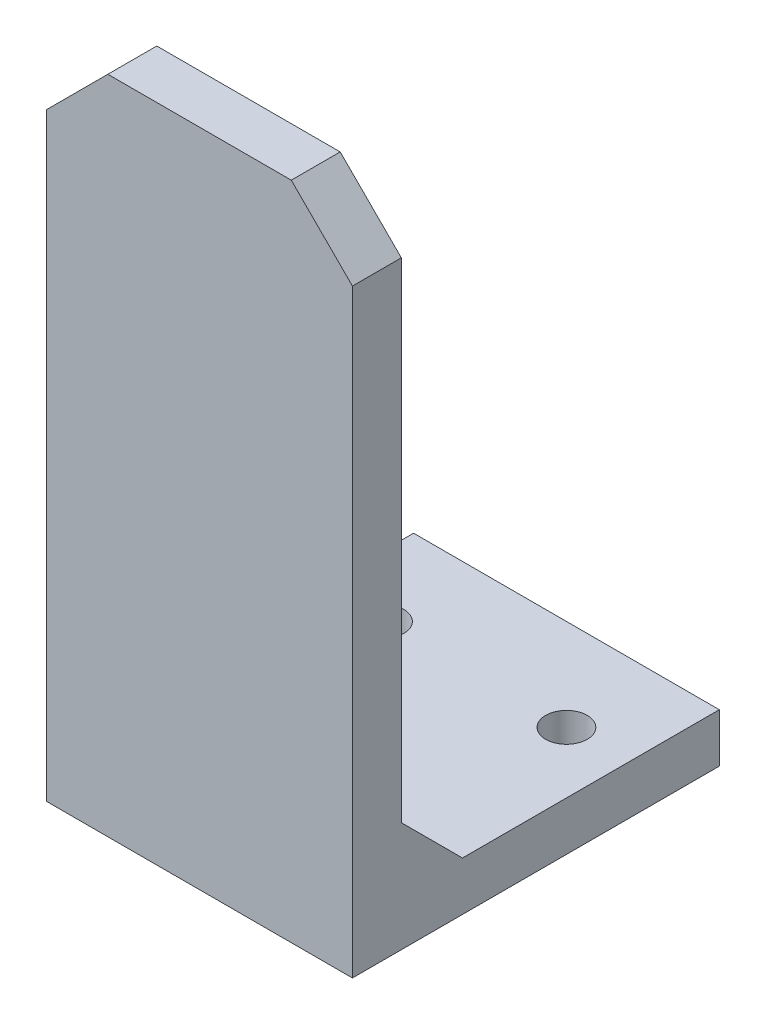
SolidWorks part; units mm, degrees
ref_plane "前视基准面" through (0, 0, 0) normal (0, 0, 1) x (1, 0, 0)
ref_plane "上视基准面" through (0, 0, 0) normal (0, 1, 0) x (1, 0, 0)
ref_plane "右视基准面" through (0, 0, 0) normal (1, 0, 0) x (0, 0, -1)
other "Configuration Table"
sketch "草图1" plane through (0, 0, 0) normal (0, 1, 0) x (1, 0, 0)
  line L1 (0, 0) -> (25, 0)
  line L2 (0, 0) -> (0, 30)
  line L3 (0, 30) -> (25, 30)
  line L4 (25, 0) -> (25, 30)
  circle A0 centre (5, 22.5) radius 1.7
  circle A1 centre (20, 22.5) radius 1.7
  point P9 (0, 0)
  point P10 (0, 0)
  point P11 (0, 0)
  dimension "D5" = 3.4
  dimension "D6" = 3.4
  dimension "D1" = 30
  dimension "D2" = 25
  dimension "D3" = 7.5
  dimension "D4" = 7.5
  dimension "D7" = 5
  dimension "D8" = 5
extrude "凸台-拉伸1" add sketch "草图1" along normal blind 4
sketch "草图2" plane through (0, 4, 0) normal (0, 1, 0) x (1, 0, 0)
  line L0 (25, 0) -> (25, 30) construction
  line L1 (0, 0) -> (25, 0)
  line L2 (0, 0) -> (0, 4)
  line L3 (0, 4) -> (25, 4)
  line L4 (25, 0) -> (25, 4)
  dimension "D1" = 4
extrude "凸台-拉伸2" add sketch "草图2" along normal blind 50
sketch "草图3" plane through (25, 0, 0) normal (1, 0, 0) x (0, 0, -1)
  line L0 (4, 4) -> (4, 9)
  line L1 (4, 54) -> (4, 4) construction
  line L2 (4, 9) -> (9, 4)
  line L3 (4, 4) -> (30, 4) construction
  line L4 (4, 4) -> (9, 4)
  dimension "D1" = 5
  dimension "D2" = 5
extrude "凸台-拉伸3" add sketch "草图3" against normal up to surface (25 mm away) up to face at (0, 19.3333, -11.3333)
sketch "草图4" plane through (0, 0, -4) normal (0, 0, -1) x (-1, 0, 0)
  line L0 (-12.5, 54) -> (-12.5, 39) construction
  line L1 (-25, 54) -> (0, 54) construction
  circle A0 centre (-12.5, 39) radius 2.9
  dimension "D2" = 5.8
  dimension "D1" = 15
extrude "凸台-拉伸4" add sketch "草图4" along normal blind 5 contours A0
chamfer "倒角2" distance 5 angle 45 2 edges at (0, 54, -2) (25, 54, -2)
